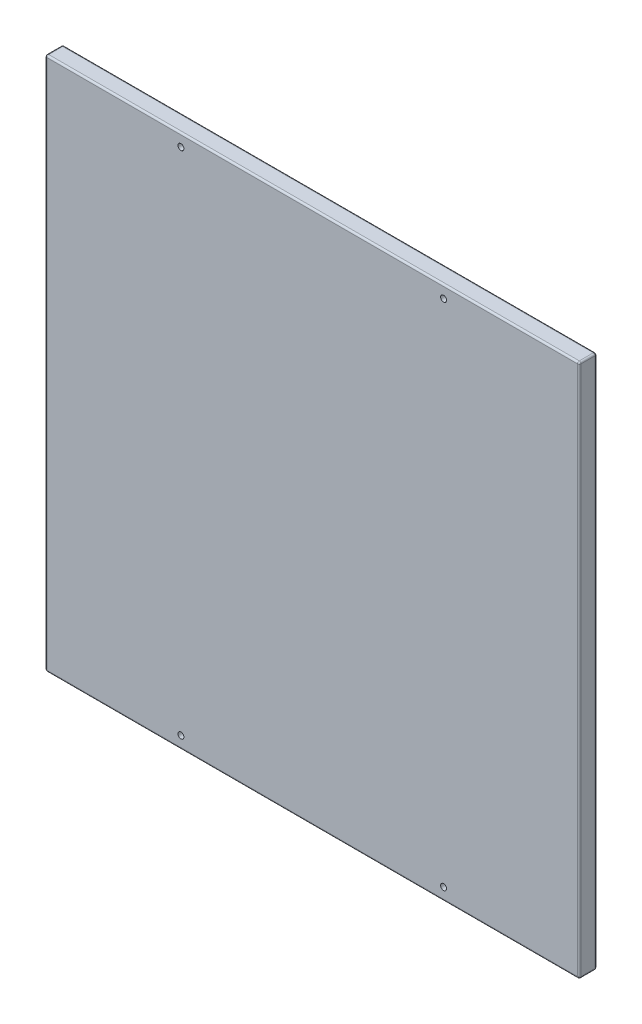
SolidWorks part; units mm, degrees
material "1060 Alloy"
ref_plane "Top Plane" through (0, 0, 0) normal (0, 0, 1) x (1, 0, 0)
ref_plane "Front Plane" through (0, 0, 0) normal (0, 1, 0) x (1, 0, 0)
ref_plane "Right Plane" through (0, 0, 0) normal (1, 0, 0) x (0, 0, -1)
sketch "Sketch1" plane through (0, 0, 0) normal (0, 0, 1) x (1, 0, 0)
  line L1 (-152.5, -152.5) -> (152.5, -152.5)
  line L2 (-152.5, -152.5) -> (-152.5, 152.5)
  line L3 (-152.5, 152.5) -> (152.5, 152.5)
  line L4 (152.5, -152.5) -> (152.5, 152.5)
  line L5 (-152.5, -152.5) -> (152.5, 152.5) construction
  line L6 (-152.5, 152.5) -> (152.5, -152.5) construction
  point P0 (0, 0)
  dimension "D1" = 305
  dimension "D2" = 305
extrude "cast aluminium" add sketch "Sketch1" along normal blind 10
fillet "corner fillets" radius 1 12 edges at (-152.5, 152.5, 5) (-152.5, -152.5, 5) (152.5, -152.5, 5) (152.5, 152.5, 5) (0, 152.5, 0) (-152.5, 0, 0) (0, -152.5, 0) (152.5, 0, 0) (0, -152.5, 10) (-152.5, 0, 10) (0, 152.5, 10) (152.5, 0, 10)
sketch "Sketch2" plane through (0, 0, 10) normal (0, 0, 1) x (1, 0, 0)
  line L1 (151.5, -152.5) -> (-151.5, -152.5) construction
  line L3 (-151.5, 152.5) -> (151.5, 152.5) construction
  circle A0 centre (-75, 145.5) radius 1.7
  circle A1 centre (75, 145.5) radius 1.7
  circle A2 centre (75, -145.5) radius 1.7
  circle A3 centre (-75, -145.5) radius 1.7
  point P8 (0, 0)
  point P9 (0, 0)
  point P10 (0, 0)
  point P15 (-2.5604, 152)
  dimension "D8" = 3.4
  dimension "D9" = 3.4
  dimension "D10" = 3.4
  dimension "D11" = 3.4
  dimension "D1" = 150
  dimension "D2" = 75
  dimension "D3" = 7
  dimension "D4" = 7
  dimension "D5" = 75
  dimension "D6" = 7
  dimension "D7" = 7
extrude "mounting holes" cut sketch "Sketch2" against normal through all
